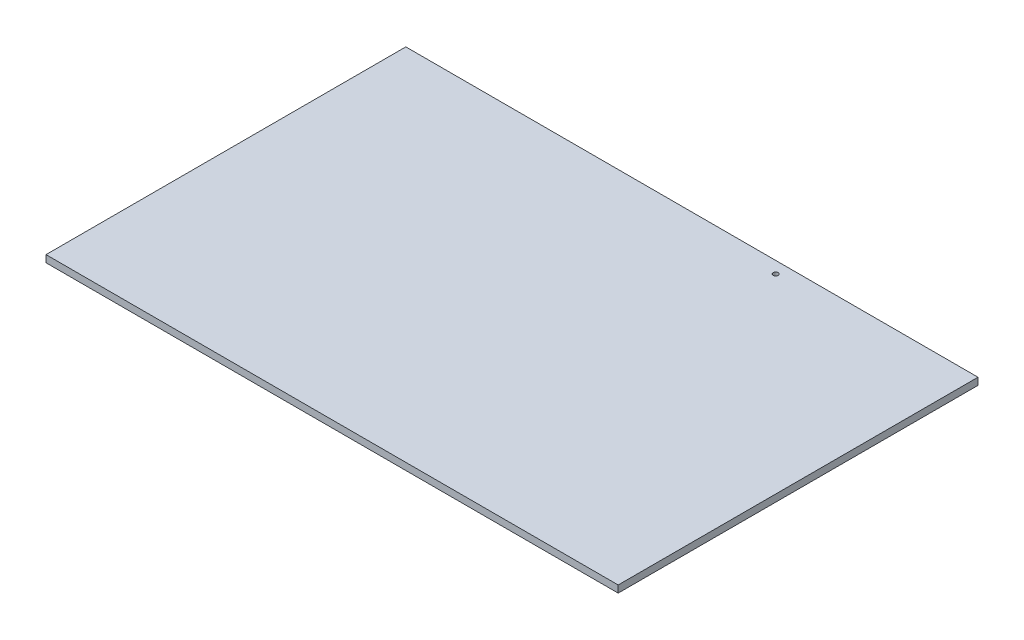
SolidWorks part; units mm, degrees
ref_plane "Front Plane" through (0, 0, 0) normal (0, 0, 1) x (1, 0, 0)
ref_plane "Top Plane" through (0, 0, 0) normal (0, 1, 0) x (1, 0, 0)
ref_plane "Right Plane" through (0, 0, 0) normal (1, 0, 0) x (0, 0, -1)
sketch "Sketch1" plane through (0, 0, 0) normal (0, 1, 0) x (1, 0, 0)
  line L1 (-677.3067, 361.6334) -> (292.6933, 361.6334)
  line L2 (-677.3067, 361.6334) -> (-677.3067, -248.3666)
  line L3 (-677.3067, -248.3666) -> (292.6933, -248.3666)
  line L4 (292.6933, 361.6334) -> (292.6933, -248.3666)
  dimension "D1" = 970
  dimension "D2" = 610
extrude "Boss-Extrude1" add sketch "Sketch1" along normal blind 12
sketch "Sketch2" plane through (0, 12, 0) normal (0, 1, 0) x (1, 0, 0)
  circle A0 centre (-30.2954, 341.622) radius 4.2339
extrude "Cut-Extrude1" cut sketch "Sketch2" against normal blind 10
